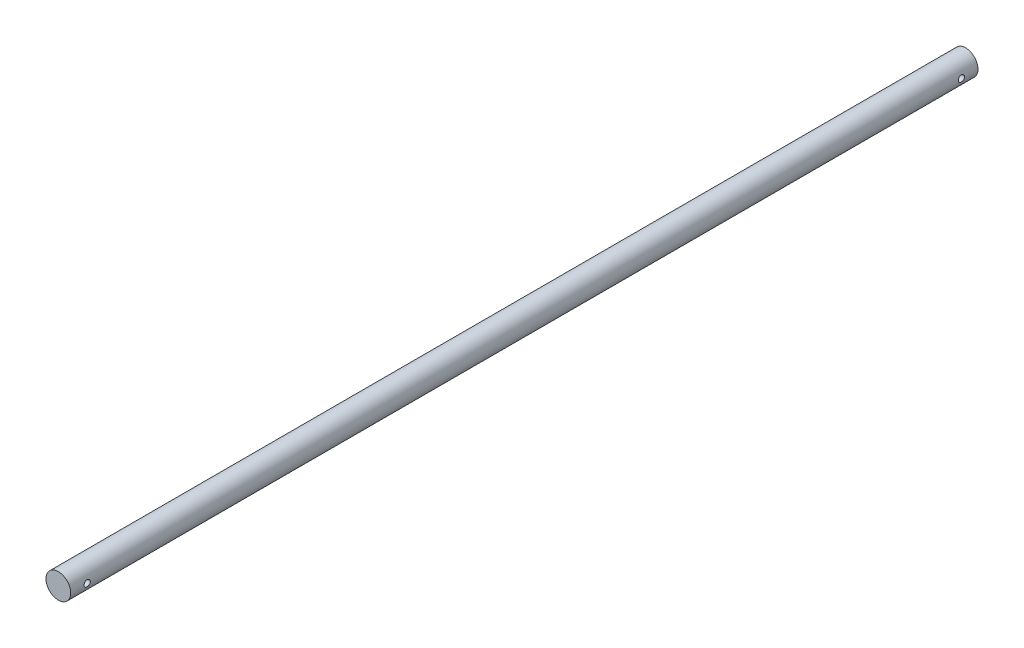
SolidWorks part; units mm, degrees
material "AISI 1020"
ref_plane "前视基准面" through (0, 0, 0) normal (0, 0, 1) x (1, 0, 0)
ref_plane "上视基准面" through (0, 0, 0) normal (0, 1, 0) x (1, 0, 0)
ref_plane "右视基准面" through (0, 0, 0) normal (1, 0, 0) x (0, 0, -1)
sketch "草图1" plane through (0, 0, 0) normal (0, 0, 1) x (1, 0, 0)
  circle A0 centre (0, 0) radius 3
  dimension "D1" = 6
extrude "凸台-拉伸1" add sketch "草图1" along normal blind 220
sketch "草图2" plane through (0, 0, 0) normal (1, 0, 0) x (0, 0, -1)
  line L0 (0, -3) -> (0, 3) construction
  line L1 (0, 0) -> (-4, 0) construction
  line L2 (-220, 3) -> (-220, -3) construction
  line L3 (-216, 0) -> (-4, 0) construction
  circle A0 centre (-4, 0) radius 0.75
  circle A1 centre (-216, 0) radius 0.75
  dimension "D1" = 1.5
  dimension "D2" = 4
  dimension "D3" = 1.5
  dimension "D4" = 4
extrude "切除-拉伸1" cut sketch "草图2" against normal through all and the other way through all
